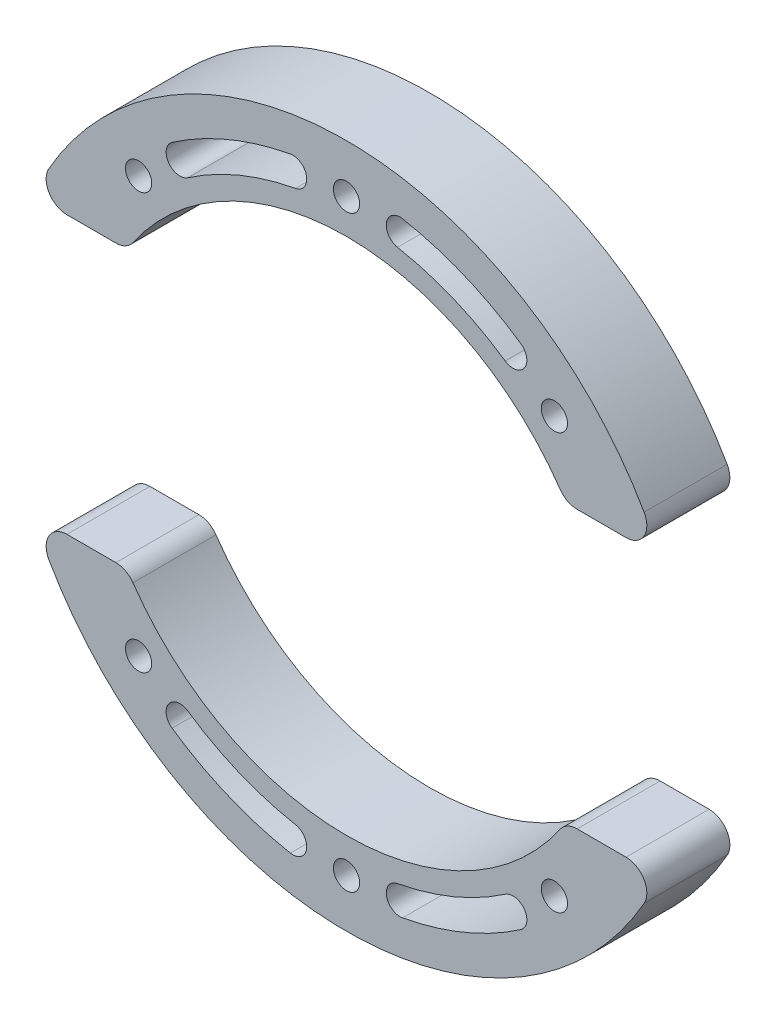
SolidWorks part; units mm, degrees
material "Thornel Mat VMA"
ref_plane "前视基准面" through (0, 0, 0) normal (0, 0, 1) x (1, 0, 0)
ref_plane "上视基准面" through (0, 0, 0) normal (0, 1, 0) x (1, 0, 0)
ref_plane "右视基准面" through (0, 0, 0) normal (1, 0, 0) x (0, 0, -1)
other "Configuration Table"
sketch "草图1" plane through (0, 0, 0) normal (0, 0, 1) x (1, 0, 0)
  line L0 (-42.5, 0) -> (42.5, 0) construction
  circle A0 centre (0, 0) radius 37.5
  circle A1 centre (0, 0) radius 42.5 construction
  circle A2 centre (0, 42.5) radius 1.9
  circle A3 centre (30.052, 30.052) radius 1.9
  circle A5 centre (30.052, -30.052) radius 1.9
  circle A6 centre (0, -42.5) radius 1.9
  circle A7 centre (-30.052, -30.052) radius 1.9
  circle A9 centre (-30.052, 30.052) radius 1.9
  circle A10 centre (-42.5, 0) radius 1.9 [skipped]
  circle A11 centre (42.5, 0) radius 1.9 [skipped]
  circle A12 centre (-42.5, 0) radius 1.9
  circle A13 centre (42.5, 0) radius 1.9
  circle A14 centre (0, 0) radius 49.5
  point P9 (0, 0)
  point P26 (0, 0)
  dimension "D1" = 5
  dimension "D2" = 85
  dimension "D5" = 3.8
  dimension "D6" = 99
  dimension "D4" = 8
extrude "凸台-拉伸1" add sketch "草图1" along normal blind 12
sketch "草图2" plane through (0, 0, 12) normal (0, 0, 1) x (1, 0, 0)
  line L0 (0, 0) -> (-30.052, 30.052) construction
  line L1 (-30.052, 30.052) -> (0, 42.5) construction
  line L2 (0, 42.5) -> (0, 0) construction
  line L3 (0, 0) -> (-15.026, 36.276) construction
  line L4 (-24.0723, 35.0254) -> (0, 0) construction
  line L5 (0, 0) -> (-7.745, 41.7883) construction
  line L6 (-16.264, 39.2649) -> (-15.026, 36.276) construction
  circle A0 centre (0, 0) radius 42.5 construction
  arc A1 (-24.0723, 35.0254) -> (-7.745, 41.7883) centre (0, 0) cw construction
  arc A2 (-8.1095, 43.7548) -> (-25.2051, 36.6736) centre (0, 0) ccw
  arc A3 (-7.3805, 39.8218) -> (-22.9395, 33.3771) centre (0, 0) ccw
  arc A4 (-7.3805, 39.8218) -> (-8.1095, 43.7548) centre (-7.745, 41.7883) ccw
  arc A5 (-25.2051, 36.6736) -> (-22.9395, 33.3771) centre (-24.0723, 35.0254) ccw
  arc A6 (7.745, 41.7883) -> (24.0723, 35.0254) centre (0, 0) cw construction
  arc A7 (25.2051, 36.6736) -> (8.1095, 43.7548) centre (0, 0) ccw
  arc A8 (22.9395, 33.3771) -> (7.3805, 39.8218) centre (0, 0) ccw
  arc A9 (22.9395, 33.3771) -> (25.2051, 36.6736) centre (24.0723, 35.0254) ccw
  arc A10 (8.1095, 43.7548) -> (7.3805, 39.8218) centre (7.745, 41.7883) ccw
  arc A21 (24.0723, -35.0254) -> (7.745, -41.7883) centre (0, 0) cw construction
  arc A22 (8.1095, -43.7548) -> (25.2051, -36.6736) centre (0, 0) ccw
  arc A23 (7.3805, -39.8218) -> (22.9395, -33.3771) centre (0, 0) ccw
  arc A24 (7.3805, -39.8218) -> (8.1095, -43.7548) centre (7.745, -41.7883) ccw
  arc A25 (25.2051, -36.6736) -> (22.9395, -33.3771) centre (24.0723, -35.0254) ccw
  arc A26 (-7.745, -41.7883) -> (-24.0723, -35.0254) centre (0, 0) cw construction
  arc A27 (-25.2051, -36.6736) -> (-8.1095, -43.7548) centre (0, 0) ccw
  arc A28 (-22.9395, -33.3771) -> (-7.3805, -39.8218) centre (0, 0) ccw
  arc A29 (-22.9395, -33.3771) -> (-25.2051, -36.6736) centre (-24.0723, -35.0254) ccw
  arc A30 (-8.1095, -43.7548) -> (-7.3805, -39.8218) centre (-7.745, -41.7883) ccw
  arc A78 (41.7883, -7.745) -> (35.0254, -24.0723) centre (0, 0) cw construction
  arc A79 (36.6736, -25.2051) -> (43.7548, -8.1095) centre (0, 0) ccw
  arc A80 (33.3771, -22.9395) -> (39.8218, -7.3805) centre (0, 0) ccw
  arc A81 (33.3771, -22.9395) -> (36.6736, -25.2051) centre (35.0254, -24.0723) ccw
  arc A82 (43.7548, -8.1095) -> (39.8218, -7.3805) centre (41.7883, -7.745) ccw
  arc A83 (35.0254, 24.0723) -> (41.7883, 7.745) centre (0, 0) cw construction
  arc A84 (43.7548, 8.1095) -> (36.6736, 25.2051) centre (0, 0) ccw
  arc A85 (39.8218, 7.3805) -> (33.3771, 22.9395) centre (0, 0) ccw
  arc A86 (39.8218, 7.3805) -> (43.7548, 8.1095) centre (41.7883, 7.745) ccw
  arc A87 (36.6736, 25.2051) -> (33.3771, 22.9395) centre (35.0254, 24.0723) ccw
  arc A88 (-35.0254, -24.0723) -> (-41.7883, -7.745) centre (0, 0) cw construction
  arc A89 (-43.7548, -8.1095) -> (-36.6736, -25.2051) centre (0, 0) ccw
  arc A90 (-39.8218, -7.3805) -> (-33.3771, -22.9395) centre (0, 0) ccw
  arc A91 (-39.8218, -7.3805) -> (-43.7548, -8.1095) centre (-41.7883, -7.745) ccw
  arc A92 (-36.6736, -25.2051) -> (-33.3771, -22.9395) centre (-35.0254, -24.0723) ccw
  arc A93 (-41.7883, 7.745) -> (-35.0254, 24.0723) centre (0, 0) cw construction
  arc A94 (-36.6736, 25.2051) -> (-43.7548, 8.1095) centre (0, 0) ccw
  arc A95 (-33.3771, 22.9395) -> (-39.8218, 7.3805) centre (0, 0) ccw
  arc A96 (-33.3771, 22.9395) -> (-36.6736, 25.2051) centre (-35.0254, 24.0723) ccw
  arc A97 (-43.7548, 8.1095) -> (-39.8218, 7.3805) centre (-41.7883, 7.745) ccw
  point P10 (-16.264, 39.2649)
  point P24 (16.264, 39.2649)
  point P32 (39.2649, -16.264)
  point P45 (16.264, -39.2649)
  point P52 (-16.264, -39.2649)
  point P60 (39.2649, 16.264)
  point P67 (-39.2649, -16.264)
  point P71 (0, 0)
  point P72 (-39.2649, 16.264)
  point P83 (39.2649, -16.264)
  point P91 (39.2649, 16.264)
  point P99 (-39.2649, -16.264)
  point P107 (-39.2649, 16.264)
  point P115 (39.2649, -16.264)
  point P123 (39.2649, 16.264)
  point P131 (-39.2649, -16.264)
  point P139 (-39.2649, 16.264)
  dimension "D1" = 2
  dimension "D2" = 12
  dimension "D3" = 8
extrude "切除-拉伸1" cut sketch "草图2" against normal blind 16
sketch "草图4" plane through (0, 0, 12) normal (0, 0, 1) x (1, 0, 0)
  line L1 (-49.5, -20) -> (49.5, -20)
  line L2 (-49.5, -20) -> (-49.5, 20)
  line L3 (-49.5, 20) -> (49.5, 20)
  line L4 (49.5, -20) -> (49.5, 20)
  line L5 (-49.5, -20) -> (49.5, 20) construction
  line L6 (-49.5, 20) -> (49.5, -20) construction
  circle A0 centre (0, 0) radius 49.5 construction
  point P0 (0, 0)
  dimension "D1" = 40
extrude "切除-拉伸2" cut sketch "草图4" against normal blind 20
fillet "圆角1" radius 3 4 edges at (31.7214, 20, 6) (-31.7214, 20, 6) (45.2797, 20, 6) (-45.2797, 20, 6)
fillet "圆角2" radius 3 4 edges at (31.7214, -20, 6) (-31.7214, -20, 6) (-45.2797, -20, 6) (45.2797, -20, 6)
